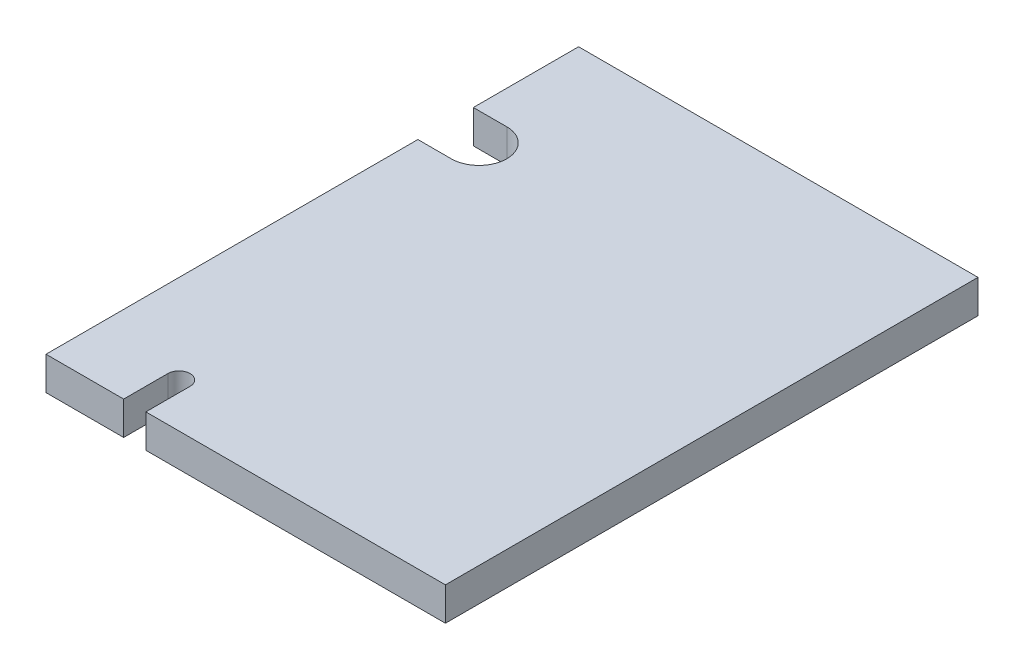
SolidWorks part; units mm, degrees
material "Pine"
ref_plane "Front Plane" through (0, 0, 0) normal (0, 0, 1) x (1, 0, 0)
ref_plane "Top Plane" through (0, 0, 0) normal (0, 1, 0) x (1, 0, 0)
ref_plane "Right Plane" through (0, 0, 0) normal (1, 0, 0) x (0, 0, -1)
sketch "Sketch1" plane through (0, 0, 0) normal (0, 1, 0) x (1, 0, 0)
  line L1 (0, 0) -> (228.6, 0)
  line L2 (0, 0) -> (0, 304.8)
  line L3 (0, 304.8) -> (228.6, 304.8)
  line L4 (228.6, 0) -> (228.6, 304.8)
  dimension "D1" = 304.8
  dimension "D2" = 228.6
extrude "Boss-Extrude2" add sketch "Sketch1" along normal blind 19.05
sketch "Sketch3" plane through (0, 0, 0) normal (0, -1, 0) x (1, 0, 0)
  line L0 (19.1255, -212.8323) -> (0, -212.8323)
  line L2 (0, -304.8) -> (0, 0) construction
  line L3 (0, -212.8323) -> (0, -244.5823)
  line L5 (0, -244.5823) -> (19.1255, -244.5823)
  line L6 (44.4495, -25.3199) -> (44.4495, 0)
  line L7 (0, 0) -> (228.6, 0) construction
  line L8 (57.1495, -25.3199) -> (57.1495, 0)
  line L9 (57.1495, 0) -> (44.4495, 0)
  arc A2 (19.1255, -212.8323) -> (35.0005, -228.7073) centre (19.1255, -228.7073) cw
  arc A3 (35.0005, -228.7073) -> (19.1255, -244.5823) centre (19.1255, -228.7073) cw
  arc A4 (44.4495, -25.3199) -> (50.7995, -31.6699) centre (50.7995, -25.3199) ccw
  arc A5 (50.7995, -31.6699) -> (57.1495, -25.3199) centre (50.7995, -25.3199) ccw
extrude "Cut-Extrude1" cut sketch "Sketch3" against normal blind 19.05
